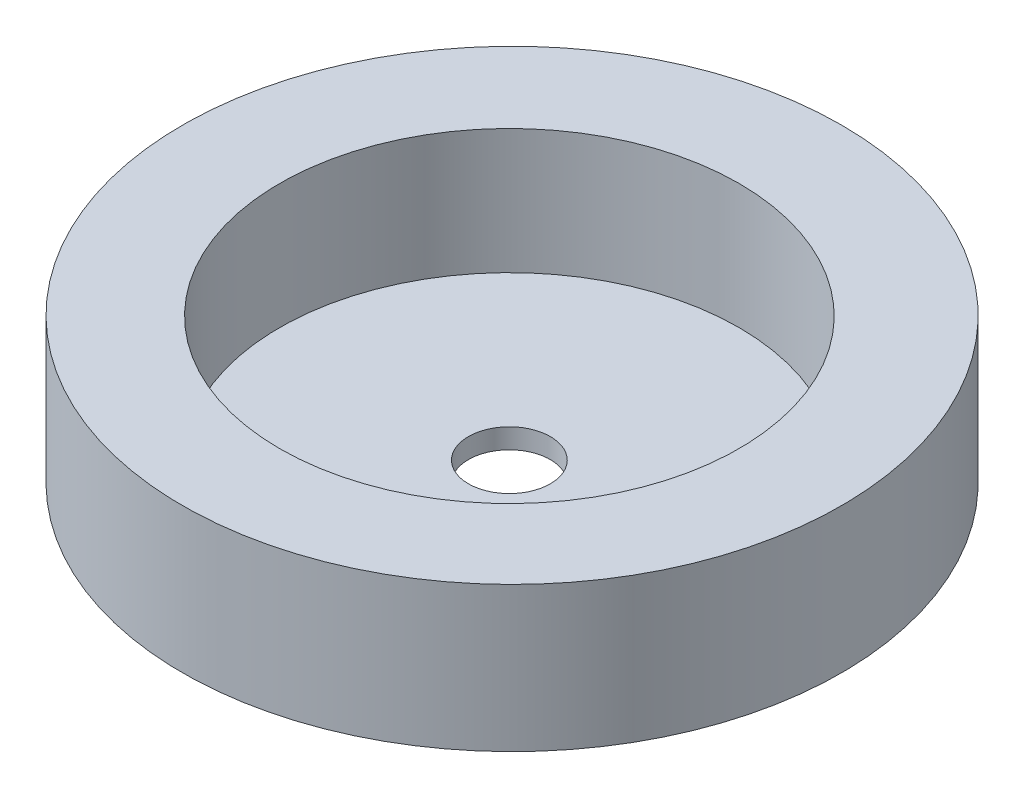
SolidWorks part; units mm, degrees
ref_plane "Front Plane" through (0, 0, 0) normal (0, 0, 1) x (1, 0, 0)
ref_plane "Top Plane" through (0, 0, 0) normal (0, 1, 0) x (1, 0, 0)
ref_plane "Right Plane" through (0, 0, 0) normal (1, 0, 0) x (0, 0, -1)
sketch "Sketch1" plane through (0, 0, 0) normal (0, 1, 0) x (1, 0, 0)
  circle A0 centre (-11.0733, 20.9976) radius 16.5
extrude "Boss-Extrude1" add sketch "Sketch1" along normal blind 7.25
sketch "Sketch2" plane through (0, 7.25, 0) normal (0, 1, 0) x (1, 0, 0)
  circle A0 centre (-11.1121, 20.9007) radius 2.05
extrude "Cut-Extrude1" cut sketch "Sketch2" against normal through all
sketch "Sketch9" plane through (0, 7.25, 0) normal (0, 1, 0) x (1, 0, 0)
  circle A0 centre (-11.1121, 20.9007) radius 11.5
extrude "Cut-Extrude2" cut sketch "Sketch9" against normal blind 6.25 contours A0
